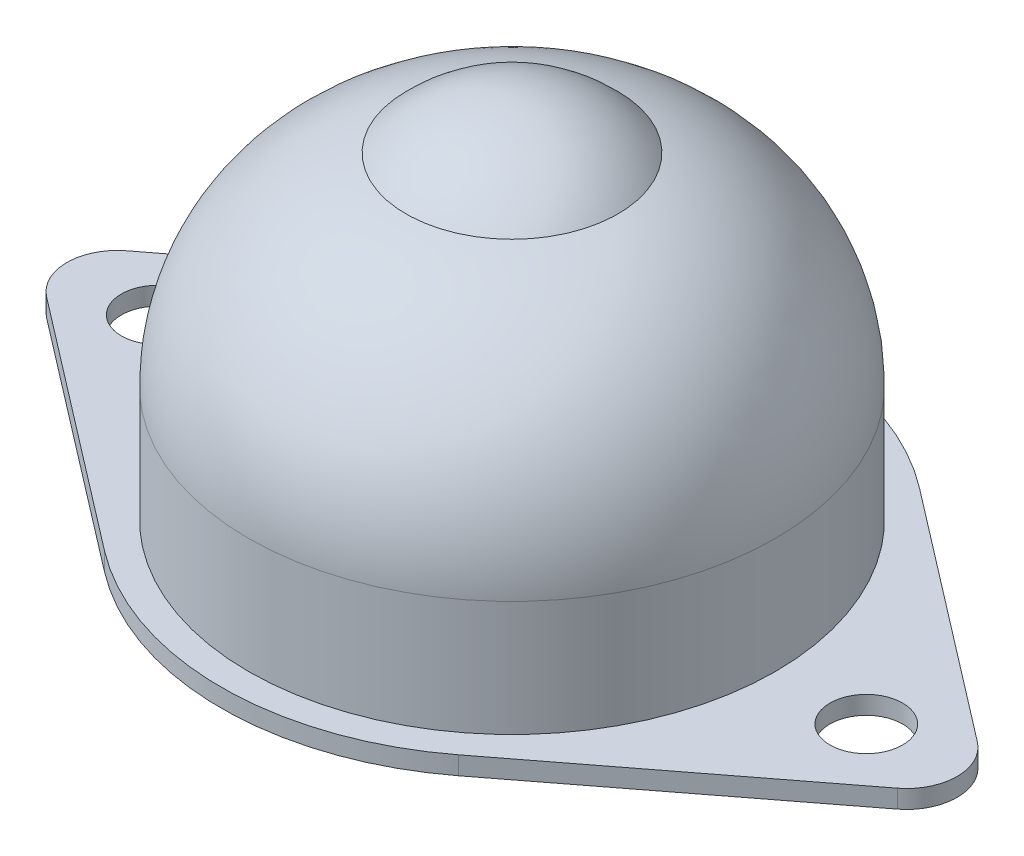
SolidWorks part; units mm, degrees
ref_plane "Front Plane" through (0, 0, 0) normal (0, 0, 1) x (1, 0, 0)
ref_plane "Top Plane" through (0, 0, 0) normal (0, 1, 0) x (1, 0, 0)
ref_plane "Right Plane" through (0, 0, 0) normal (1, 0, 0) x (0, 0, -1)
sketch "Sketch1" plane through (0, 0, 0) normal (0, 1, 0) x (1, 0, 0)
  line L0 (-57.0461, 0) -> (52.9023, 0) construction
  line L1 (0, 32.112) -> (0, -34.8772) construction
  line L2 (-23.4147, 2.2009) -> (-9.7402, 12.6937)
  line L3 (-23.4147, -2.2009) -> (-9.7402, -12.6937)
  line L4 (23.4147, -2.2009) -> (9.7402, -12.6937)
  line L5 (23.4147, 2.2009) -> (9.7402, 12.6937)
  arc A0 (-9.7402, -12.6937) -> (9.7402, -12.6937) centre (0, 0) ccw
  circle A1 centre (-19.5, 0) radius 2
  arc A2 (-23.4147, 2.2009) -> (-23.4147, -2.2009) centre (-21.7259, 0) ccw
  arc A3 (23.4147, 2.2009) -> (23.4147, -2.2009) centre (21.7259, 0) cw
  circle A4 centre (19.5, 0) radius 2
  arc A5 (9.7402, 12.6937) -> (-9.7402, 12.6937) centre (0, 0) ccw
  point P9 (-24.5, 0)
  point P19 (24.5, 0)
  dimension "D1" = 32
  dimension "D2" = 4
  dimension "D3" = 19.5
  dimension "D4" = 24.5
  dimension "D5" = 37.5
extrude "Boss-Extrude1" add sketch "Sketch1" along normal blind 1
sketch "Sketch2" plane through (0, 0, 0) normal (0, 0, 1) x (1, 0, 0)
  line L0 (0, 0) -> (0, 6.082) construction
  line L2 (0, 6.082) -> (0, 1)
  line L3 (-14.5, 7.3451) -> (-14.5, 1)
  line L4 (9.7402, 1) -> (-9.7402, 1) construction
  line L5 (-14.5, 1) -> (0, 1)
  line L6 (-9.7402, 0) -> (9.7402, 0) construction
  line L7 (0, 21) -> (0, 6.082)
  line L8 (-19.7798, 21) -> (0, 21) construction
  line L9 (-3.8874, 19.9946) -> (-23.999, 8.8466) construction
  arc A2 (0, 21) -> (-5.8358, 18.4806) centre (0, 12.9815) ccw
  arc A3 (-5.8358, 18.4806) -> (-14.5, 7.3451) centre (-3.0121, 7.3451) ccw
  point P13 (0, 21)
  dimension "D1" = 14.5
  dimension "D4" = 29
  dimension "D5" = 21
revolve "Revolve1" add sketch "Sketch2" angle 360 about L0
